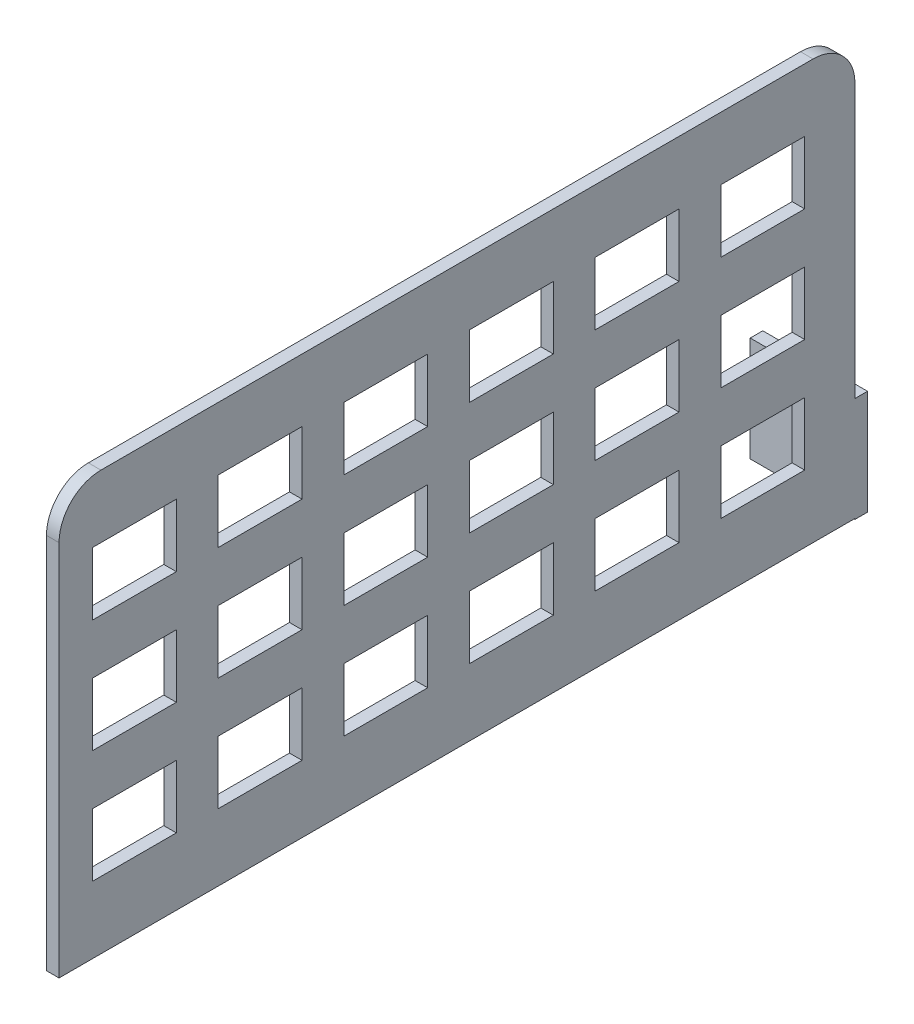
SolidWorks part; units mm, degrees
ref_plane "前视基准面" through (0, 0, 0) normal (0, 0, 1) x (1, 0, 0)
ref_plane "上视基准面" through (0, 0, 0) normal (0, 1, 0) x (1, 0, 0)
ref_plane "右视基准面" through (0, 0, 0) normal (1, 0, 0) x (0, 0, -1)
other "Configuration Table"
sketch "草图1" plane through (0, 0, 0) normal (0, 0, 1) x (1, 0, 0)
  line L0 (-112.6412, -73.6485) -> (-112.6412, -48.6485)
  line L1 (-112.6412, -73.6485) -> (-87.6412, -73.6485)
  line L2 (-112.6412, -48.6485) -> (-87.6412, -48.6485)
  line L3 (-87.6412, -73.6485) -> (-87.6412, -48.6485)
extrude "凸台-拉伸1" add sketch "草图1" along normal blind 3
sketch "草图2" plane through (0, 0, 3) normal (0, 0, 1) x (1, 0, 0)
  line L0 (-87.6412, -73.4528) -> (-87.6412, 26.5472)
  line L1 (-87.6412, -73.4528) -> (-90.6412, -73.4528)
  line L2 (-87.6412, 26.5472) -> (-90.6412, 26.5472)
  line L3 (-90.6412, -73.4528) -> (-90.6412, 26.5472)
  line L5 (-87.6412, -73.6485) -> (-87.6412, -48.6485) construction
  dimension "D1" = 100
  dimension "D2" = 3
extrude "凸台-拉伸2" add sketch "草图2" along normal blind 190
fillet "圆角1" radius 10 1 edges at (-90.6412, -61.0507, 3)
sketch "草图3" plane through (-87.6412, 0, 0) normal (1, 0, 0) x (0, 0, -1)
  line L83 (-35, 11.5472) -> (-15, 11.5472)
  line L84 (-35, 11.5472) -> (-35, -3.4528)
  line L85 (-35, -3.4528) -> (-15, -3.4528)
  line L86 (-15, 11.5472) -> (-15, -3.4528)
  line L152 (-65, 11.5472) -> (-65, -3.4528)
  line L153 (-65, 11.5472) -> (-45, 11.5472)
  line L154 (-45, 11.5472) -> (-45, -3.4528)
  line L155 (-65, -3.4528) -> (-45, -3.4528)
  line L156 (-95, 11.5472) -> (-95, -3.4528)
  line L157 (-95, 11.5472) -> (-75, 11.5472)
  line L158 (-75, 11.5472) -> (-75, -3.4528)
  line L159 (-95, -3.4528) -> (-75, -3.4528)
  line L160 (-125, 11.5472) -> (-125, -3.4528)
  line L161 (-125, 11.5472) -> (-105, 11.5472)
  line L162 (-105, 11.5472) -> (-105, -3.4528)
  line L163 (-125, -3.4528) -> (-105, -3.4528)
  line L164 (-155, 11.5472) -> (-155, -3.4528)
  line L165 (-155, 11.5472) -> (-135, 11.5472)
  line L166 (-135, 11.5472) -> (-135, -3.4528)
  line L167 (-155, -3.4528) -> (-135, -3.4528)
  line L168 (-185, 11.5472) -> (-185, -3.4528)
  line L169 (-185, 11.5472) -> (-165, 11.5472)
  line L170 (-165, 11.5472) -> (-165, -3.4528)
  line L171 (-185, -3.4528) -> (-165, -3.4528)
  line L172 (-65, -15.4528) -> (-65, -30.4528)
  line L173 (-65, -15.4528) -> (-45, -15.4528)
  line L174 (-45, -15.4528) -> (-45, -30.4528)
  line L175 (-65, -30.4528) -> (-45, -30.4528)
  line L176 (-95, -15.4528) -> (-95, -30.4528)
  line L177 (-95, -15.4528) -> (-75, -15.4528)
  line L178 (-75, -15.4528) -> (-75, -30.4528)
  line L179 (-95, -30.4528) -> (-75, -30.4528)
  line L180 (-125, -15.4528) -> (-125, -30.4528)
  line L181 (-125, -15.4528) -> (-105, -15.4528)
  line L182 (-105, -15.4528) -> (-105, -30.4528)
  line L183 (-125, -30.4528) -> (-105, -30.4528)
  line L184 (-155, -15.4528) -> (-155, -30.4528)
  line L185 (-155, -15.4528) -> (-135, -15.4528)
  line L186 (-135, -15.4528) -> (-135, -30.4528)
  line L187 (-155, -30.4528) -> (-135, -30.4528)
  line L188 (-185, -15.4528) -> (-185, -30.4528)
  line L189 (-185, -15.4528) -> (-165, -15.4528)
  line L190 (-165, -15.4528) -> (-165, -30.4528)
  line L191 (-185, -30.4528) -> (-165, -30.4528)
  line L192 (-65, -42.4528) -> (-65, -57.4528)
  line L193 (-65, -42.4528) -> (-45, -42.4528)
  line L194 (-45, -42.4528) -> (-45, -57.4528)
  line L195 (-65, -57.4528) -> (-45, -57.4528)
  line L196 (-95, -42.4528) -> (-95, -57.4528)
  line L197 (-95, -42.4528) -> (-75, -42.4528)
  line L198 (-75, -42.4528) -> (-75, -57.4528)
  line L199 (-95, -57.4528) -> (-75, -57.4528)
  line L200 (-125, -42.4528) -> (-125, -57.4528)
  line L201 (-125, -42.4528) -> (-105, -42.4528)
  line L202 (-105, -42.4528) -> (-105, -57.4528)
  line L203 (-125, -57.4528) -> (-105, -57.4528)
  line L204 (-155, -42.4528) -> (-155, -57.4528)
  line L205 (-155, -42.4528) -> (-135, -42.4528)
  line L206 (-135, -42.4528) -> (-135, -57.4528)
  line L207 (-155, -57.4528) -> (-135, -57.4528)
  line L208 (-185, -42.4528) -> (-185, -57.4528)
  line L209 (-185, -42.4528) -> (-165, -42.4528)
  line L210 (-165, -42.4528) -> (-165, -57.4528)
  line L211 (-185, -57.4528) -> (-165, -57.4528)
  line L212 (-35, -15.4528) -> (-35, -30.4528)
  line L213 (-35, -15.4528) -> (-15, -15.4528)
  line L214 (-15, -15.4528) -> (-15, -30.4528)
  line L215 (-35, -30.4528) -> (-15, -30.4528)
  line L216 (-35, -42.4528) -> (-35, -57.4528)
  line L217 (-35, -42.4528) -> (-15, -42.4528)
  line L218 (-15, -42.4528) -> (-15, -57.4528)
  line L219 (-35, -57.4528) -> (-15, -57.4528)
  line L220 (-193, 26.5472) -> (-3, 26.5472) construction
  line L221 (-3, -48.6485) -> (-3, 26.5472) construction
  dimension "D1" = 20
  dimension "D3" = 6
  dimension "D4" = 3
  dimension "D5" = 15
  dimension "D2" = 15
  dimension "D6" = 12
extrude "切除-拉伸2" cut sketch "草图3" against normal blind 10
fillet "圆角2" radius 10 1 edges at (-89.1412, 26.5472, 193)
fillet "圆角3" radius 10 1 edges at (-89.1412, 26.5472, 3)
